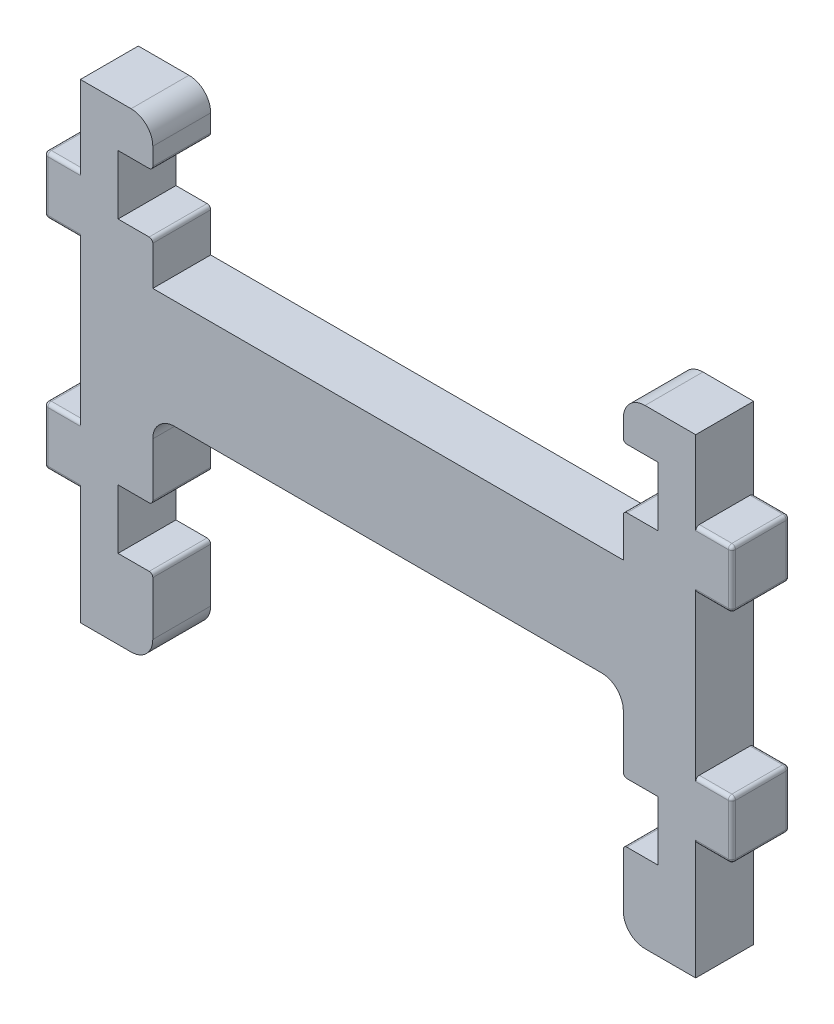
SolidWorks part; units mm, degrees
ref_plane "Alzado" through (0, 0, 0) normal (0, 0, 1) x (1, 0, 0)
ref_plane "Planta" through (0, 0, 0) normal (0, 1, 0) x (1, 0, 0)
ref_plane "Vista lateral" through (0, 0, 0) normal (1, 0, 0) x (0, 0, -1)
sketch "Croquis1" plane through (0, 0, 0) normal (0, 0, 1) x (1, 0, 0)
  line L1 (42.5, -32.5) -> (-42.5, -32.5)
  line L2 (42.5, -32.5) -> (42.5, 32.5)
  line L3 (42.5, 32.5) -> (-42.5, 32.5)
  line L4 (-42.5, -32.5) -> (-42.5, 32.5)
  line L5 (42.5, -32.5) -> (-42.5, 32.5) construction
  line L6 (42.5, 32.5) -> (-42.5, -32.5) construction
  point P0 (0, 0)
  dimension "D1" = 85
  dimension "D2" = 65
extrude "Saliente-Extruir1" add sketch "Croquis1" along normal blind 8
sketch "Croquis2" plane through (0, 0, 8) normal (0, 0, 1) x (1, 0, 0)
  line L0 (42.5, 32.5) -> (-42.5, 32.5) construction
  line L1 (-32.5, 32.5) -> (32.5, 32.5)
  line L2 (-32.5, 32.5) -> (-32.5, 12.5)
  line L3 (-32.5, 12.5) -> (32.5, 12.5)
  line L4 (32.5, 32.5) -> (32.5, 12.5)
  point P6 (0, 12.5)
  dimension "D1" = 20
  dimension "D2" = 65
extrude "Cortar-Extruir1" cut sketch "Croquis2" against normal blind 8
sketch "Croquis3" plane through (0, 0, 8) normal (0, 0, 1) x (1, 0, 0)
  line L0 (-42.5, -32.5) -> (42.5, -32.5) construction
  line L1 (-32.5, -32.5) -> (32.5, -32.5)
  line L2 (-32.5, -32.5) -> (-32.5, -2.5)
  line L3 (-32.5, -2.5) -> (32.5, -2.5)
  line L4 (32.5, -32.5) -> (32.5, -2.5)
  point P6 (0, -2.5)
  dimension "D1" = 65
  dimension "D2" = 30
extrude "Cortar-Extruir2" cut sketch "Croquis3" against normal blind 8
fillet "Redondeo1" radius 3 2 edges at (32.5, -2.5, 4) (-32.5, -2.5, 4)
sketch "Croquis4" plane through (-42.5, 0, 0) normal (-1, 0, 0) x (0, 0, 1)
  line L0 (0, 32.5) -> (0, -32.5) construction
  line L1 (0, -8.5) -> (8, -8.5)
  line L2 (0, -8.5) -> (0, -16.5)
  line L3 (0, -16.5) -> (8, -16.5)
  line L4 (8, -8.5) -> (8, -16.5)
  line L5 (8, 32.5) -> (8, -32.5) construction
  line L6 (8, -32.5) -> (0, -32.5) construction
  line L7 (0, 21.5) -> (8, 21.5)
  line L8 (0, 21.5) -> (0, 13.5)
  line L9 (0, 13.5) -> (8, 13.5)
  line L10 (8, 21.5) -> (8, 13.5)
  point P12 (0, -12.5)
  point P15 (0, 17.5)
  dimension "D1" = 8
  dimension "D2" = 8
  dimension "D3" = 20
  dimension "D4" = 30
extrude "Saliente-Extruir2" add sketch "Croquis4" along normal blind 5
fillet "Redondeo2" radius 0.5 16 edges at (-47.5, -8.5, 4) (-47.5, -12.5, 8) (-47.5, -16.5, 4) (-47.5, -12.5, 0) (-47.5, 21.5, 4) (-47.5, 17.5, 8) (-47.5, 13.5, 4) (-47.5, 17.5, 0) (-45, -16.5, 0) (-45, -16.5, 8) (-45, -8.5, 8) (-45, -8.5, 0) (-45, 13.5, 0) (-45, 21.5, 0) (-45, 13.5, 8) (-45, 21.5, 8)
mirror "Simetría1" about plane through (0, 0, 0) normal (1, 0, 0) of "Redondeo2", "Saliente-Extruir2"
fillet "Redondeo3" radius 3 4 edges at (32.5, 32.5, 4) (-32.5, 32.5, 4) (32.5, -32.5, 4) (-32.5, -32.5, 4)
sketch "Croquis5" plane through (0, 0, 8) normal (0, 0, 1) x (1, 0, 0)
  line L0 (-32.5, 29.5) -> (-32.5, 12.5) construction
  line L1 (-32.5, 26.6) -> (-37.3, 26.6)
  line L2 (-32.5, 26.6) -> (-32.5, 18.4)
  line L3 (-32.5, 18.4) -> (-37.3, 18.4)
  line L4 (-37.3, 26.6) -> (-37.3, 18.4)
  line L5 (-32.5, -5.5) -> (-32.5, -29.5) construction
  line L6 (-32.5, -13.4) -> (-37.3, -13.4)
  line L7 (-32.5, -13.4) -> (-32.5, -21.6)
  line L8 (-32.5, -21.6) -> (-37.3, -21.6)
  line L9 (-37.3, -13.4) -> (-37.3, -21.6)
  line L10 (-32.5, 12.5) -> (32.5, 12.5) construction
  line L11 (-42.5, -32.5) -> (-35.5, -32.5) construction
  line L12 (0, 0) -> (0, 6.8435) construction
  line L13 (37.3, -13.4) -> (37.3, -21.6)
  line L14 (32.5, -21.6) -> (37.3, -21.6)
  line L15 (32.5, -13.4) -> (32.5, -21.6)
  line L16 (32.5, -13.4) -> (37.3, -13.4)
  line L17 (37.3, 26.6) -> (37.3, 18.4)
  line L18 (32.5, 18.4) -> (37.3, 18.4)
  line L19 (32.5, 26.6) -> (32.5, 18.4)
  line L20 (32.5, 26.6) -> (37.3, 26.6)
  point P12 (-32.5, 22.5)
  point P15 (-32.5, -17.5)
  dimension "D1" = 4.8
  dimension "D2" = 8.2
  dimension "D3" = 8.2
  dimension "D4" = 4.8
  dimension "D5" = 10
  dimension "D6" = 15
extrude "Cortar-Extruir3" cut sketch "Croquis5" against normal through all
fillet "Redondeo4" radius 0.5 8 edges at (32.5, -21.6, 4) (32.5, -13.4, 4) (32.5, 18.4, 4) (32.5, 26.6, 4) (-32.5, -21.6, 4) (-32.5, -13.4, 4) (-32.5, 26.6, 4) (-32.5, 18.4, 4)
